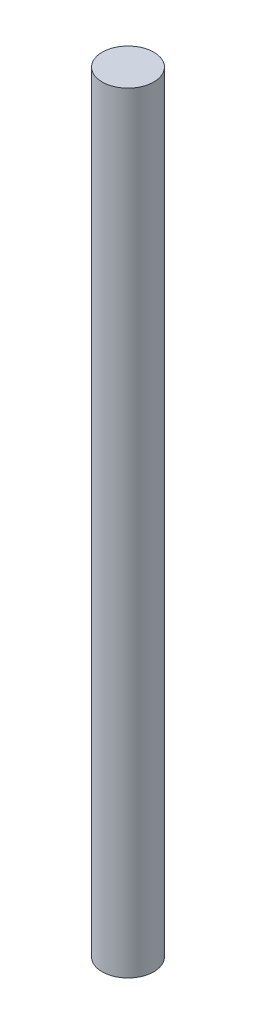
SolidWorks part; units mm, degrees
ref_plane "前视基准面" through (0, 0, 0) normal (0, 0, 1) x (1, 0, 0)
ref_plane "上视基准面" through (0, 0, 0) normal (0, 1, 0) x (1, 0, 0)
ref_plane "右视基准面" through (0, 0, 0) normal (1, 0, 0) x (0, 0, -1)
other "Configuration Table"
sketch "草图1" plane through (0, 0, 0) normal (0, 1, 0) x (1, 0, 0)
  circle A0 centre (0, 0) radius 1.4
  point P0 (-90.6464, 22.0667)
  dimension "D1" = 2.8
extrude "凸台-拉伸1" add sketch "草图1" along normal blind 41.8
